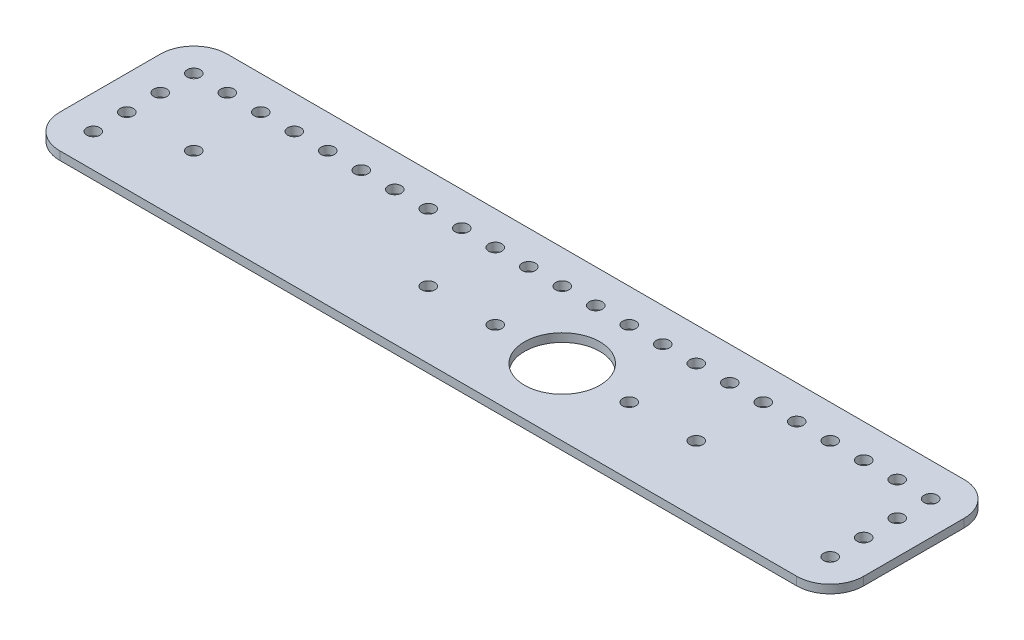
SolidWorks part; units mm, degrees
material "6061 Alloy"
ref_plane "Front Plane" through (0, 0, 0) normal (0, 0, 1) x (1, 0, 0)
ref_plane "Top Plane" through (0, 0, 0) normal (0, 1, 0) x (1, 0, 0)
ref_plane "Right Plane" through (0, 0, 0) normal (1, 0, 0) x (0, 0, -1)
sketch "Sketch1" plane through (0, 0, 0) normal (0, 1, 0) x (1, 0, 0)
  line L0 (0, 0) -> (0, 63.5)
  line L1 (0, 63.5) -> (304.8, 63.5)
  line L2 (304.8, 63.5) -> (304.8, 0)
  line L3 (304.8, 0) -> (279.4, 0)
  line L4 (279.4, 0) -> (279.4, 38.1)
  line L5 (279.4, 38.1) -> (25.4, 38.1)
  line L6 (25.4, 38.1) -> (25.4, 0)
  line L7 (25.4, 0) -> (0, 0)
  line L8 (12.7, 50.8) -> (25.4, 50.8) construction
  line L9 (12.7, 50.8) -> (12.7, 38.1) construction
  line L10 (25.4, 0) -> (279.4, 0)
  circle A0 centre (12.7, 50.8) radius 2.4892
  circle A1 centre (25.4, 50.8) radius 2.4892
  circle A2 centre (38.1, 50.8) radius 2.4892
  circle A3 centre (50.8, 50.8) radius 2.4892
  circle A4 centre (63.5, 50.8) radius 2.4892
  circle A5 centre (76.2, 50.8) radius 2.4892
  circle A6 centre (88.9, 50.8) radius 2.4892
  circle A7 centre (101.6, 50.8) radius 2.4892
  circle A8 centre (114.3, 50.8) radius 2.4892
  circle A9 centre (127, 50.8) radius 2.4892
  circle A10 centre (139.7, 50.8) radius 2.4892
  circle A11 centre (152.4, 50.8) radius 2.4892
  circle A12 centre (165.1, 50.8) radius 2.4892
  circle A13 centre (177.8, 50.8) radius 2.4892
  circle A14 centre (190.5, 50.8) radius 2.4892
  circle A15 centre (203.2, 50.8) radius 2.4892
  circle A16 centre (215.9, 50.8) radius 2.4892
  circle A17 centre (228.6, 50.8) radius 2.4892
  circle A18 centre (241.3, 50.8) radius 2.4892
  circle A19 centre (254, 50.8) radius 2.4892
  circle A20 centre (266.7, 50.8) radius 2.4892
  circle A21 centre (279.4, 50.8) radius 2.4892
  circle A22 centre (292.1, 50.8) radius 2.4892
  circle A23 centre (12.7, 38.1) radius 2.4892
  circle A24 centre (292.1, 38.1) radius 2.4892
  circle A25 centre (12.7, 25.4) radius 2.4892
  circle A26 centre (292.1, 25.4) radius 2.4892
  circle A27 centre (12.7, 12.7) radius 2.4892
  circle A28 centre (292.1, 12.7) radius 2.4892
  dimension "D6" = 12.7
  dimension "D7" = 12.7
  dimension "D8" = 4.9784
  dimension "D1" = 25.4
  dimension "D2" = 304.8
  dimension "D3" = 25.4
  dimension "D4" = 25.4
  dimension "D5" = 63.5
  dimension "D10" = 12.7
  dimension "D12" = 12.7
  dimension "D9" = 23
  dimension "D11" = 4
extrude "Boss-Extrude1" add sketch "Sketch1" along normal blind 3.175
sketch "Sketch2" plane through (0, 3.175, 0) normal (0, 1, 0) x (1, 0, 0)
  line B0 (68.7873, 5.0409) -> (202.7488, 5.0409)
  line B1 (202.7488, 74.8909) -> (68.7873, 74.8909)
  circle B2 centre (237.8973, 39.9659) radius 2.54
  circle B3 centre (221.6286, 39.9659) radius 2.54
  arc B4 (216.9621, 58.6686) -> (222.2457, 55.8409) centre (222.2457, 62.1909) ccw
  arc B5 (68.7873, 74.8909) -> (63.5038, 72.0633) centre (68.7873, 68.5409) ccw
  arc B6 (47.3973, 62.1909) -> (41.0473, 55.8409) centre (47.3973, 55.8409) ccw
  circle B7 centre (187.0973, 39.9659) radius 14.2875
  circle B8 centre (152.5659, 39.9659) radius 2.54
  circle B9 centre (107.7223, 62.1909) radius 2.4892
  circle B10 centre (136.2973, 39.9659) radius 2.54
  circle B11 centre (107.7223, 17.7409) radius 2.4892
  circle B12 centre (69.6223, 17.7409) radius 2.4892
  circle B13 centre (47.3973, 39.9659) radius 2.54
  circle B14 centre (69.6223, 62.1909) radius 2.4892
sketch_block_instance "Block-new elevator gusset-1"
sketch_block "Block-new elevator gusset"
sketch "Sketch3" plane through (0, 3.175, 0) normal (0, 1, 0) x (1, 0, 0)
  line L0 (304.8, 63.5) -> (304.8, 0) construction
  line L2 (0, 63.5) -> (304.8, 63.5) construction
  circle A0 centre (60.3142, 47.625) radius 2.4892 construction
  circle A1 centre (98.4142, 47.625) radius 2.4892 construction
  circle A2 centre (126.9892, 25.4) radius 2.4892
  circle A3 centre (143.2579, 25.4) radius 2.4892 construction
  circle A4 centre (177.7892, 25.4) radius 14.2875
  circle A5 centre (212.3206, 25.4) radius 2.4892 construction
  circle A6 centre (228.5892, 25.4) radius 2.4892
  circle A7 centre (98.4142, 3.175) radius 2.4892 construction
  circle A8 centre (60.3142, 3.175) radius 2.4892 construction
  circle A9 centre (38.0892, 25.4) radius 2.4892
  circle A10 centre (152.3892, 25.4) radius 2.4892
  circle A11 centre (203.1892, 25.4) radius 2.4892
  dimension "D1" = 28.575
  dimension "D2" = 4.9784
  dimension "D3" = 44.45
  dimension "D4" = 38.1
  dimension "D5" = 22.225
  dimension "D6" = 16.2686
  dimension "D7" = 16.2686
  dimension "D8" = 34.5314
  dimension "D9" = 34.5314
  dimension "D10" = 28.575
  dimension "D11" = 22.225
  dimension "D12" = 127.0108
  dimension "D13" = 38.1
  dimension "D14" = 25.4
  dimension "D15" = 25.4
extrude "Cut-Extrude1" cut sketch "Sketch3" against normal through all
fillet "Fillet1" radius 12.7 4 edges at (0, 1.5875, -63.5) (304.8, 1.5875, -63.5) (304.8, 1.5875, 0) (0, 1.5875, 0)
sketch "Sketch4" plane through (0, 3.175, 0) normal (0, -1, 0) x (1, 0, 0)
  line L0 (-1033.1809, 0) -> (48966.8191, 0) construction
  line L1 (0, -968.3084) -> (0, 49031.6916) construction
  point P3 (0, 0)
